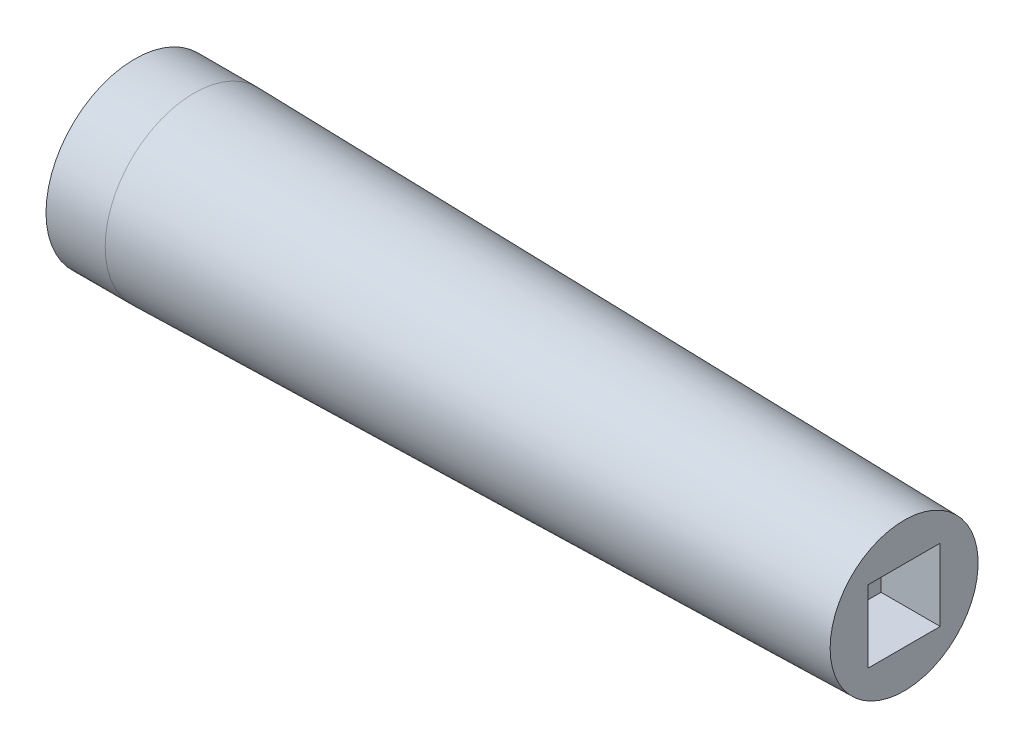
SolidWorks part; units mm, degrees
ref_plane "Front Plane" through (0, 0, 0) normal (0, 0, 1) x (1, 0, 0)
ref_plane "Top Plane" through (0, 0, 0) normal (0, 1, 0) x (1, 0, 0)
ref_plane "Right Plane" through (0, 0, 0) normal (1, 0, 0) x (0, 0, -1)
sketch "Sketch1" plane through (0, 0, 0) normal (0, 1, 0) x (1, 0, 0)
  line L0 (0, 0) -> (165.1, 0)
  line L1 (165.1, 0) -> (165.1, 15.88)
  line L2 (165.1, 15.88) -> (12.7, 19.05)
  line L3 (12.7, 19.05) -> (0, 19.05)
  line L4 (0, 19.05) -> (0, 0)
  dimension "D1" = 165.1
  dimension "D2" = 15.88
  dimension "D3" = 12.7
  dimension "D4" = 19.05
revolve "Revolve1" add sketch "Sketch1" angle 360 about L0
sketch "Sketch2" plane through (165.1, 0, 0) normal (1, 0, 0) x (0, 0, -1)
  line L1 (7.745, 7.745) -> (-7.745, 7.745)
  line L2 (7.745, 7.745) -> (7.745, -7.745)
  line L3 (7.745, -7.745) -> (-7.745, -7.745)
  line L4 (-7.745, 7.745) -> (-7.745, -7.745)
  line L5 (7.745, 7.745) -> (-7.745, -7.745) construction
  line L6 (7.745, -7.745) -> (-7.745, 7.745) construction
  point P0 (0, 0)
  dimension "D1" = 15.49
extrude "Cut-Extrude1" cut sketch "Sketch2" against normal blind 12.7
